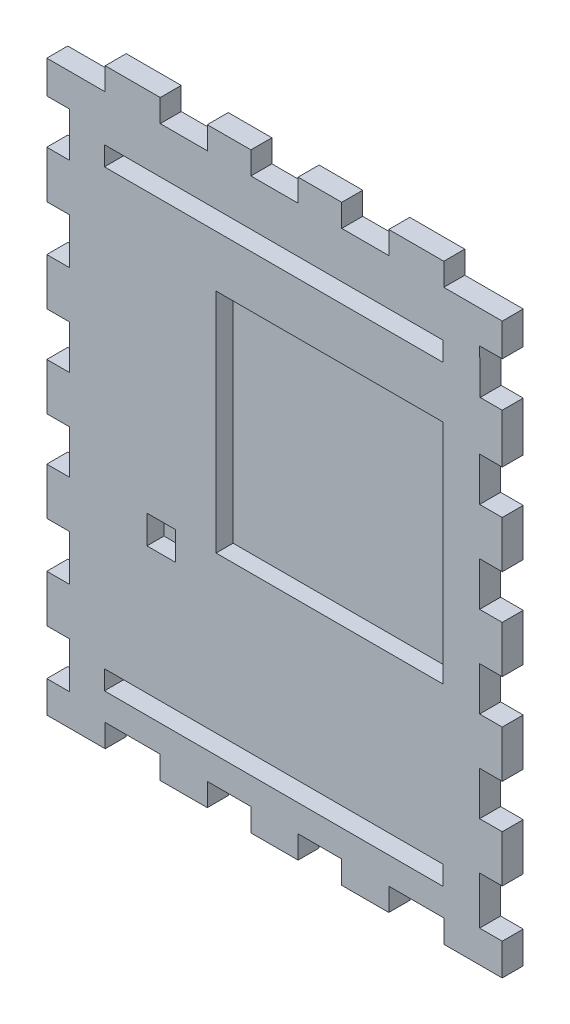
SolidWorks part; units mm, degrees
ref_plane "Front Plane" through (0, 0, 0) normal (0, 0, 1) x (1, 0, 0)
ref_plane "Top Plane" through (0, 0, 0) normal (0, 1, 0) x (1, 0, 0)
ref_plane "Right Plane" through (0, 0, 0) normal (1, 0, 0) x (0, 0, -1)
sketch "Model" plane through (0, 0, 0) normal (0, 0, 1) x (1, 0, 0)
  line L0 (11.6457, 131.1853) -> (7.6593, 131.1853)
  line L1 (7.6593, 131.1853) -> (7.6593, 139.4756)
  line L2 (7.6593, 139.4756) -> (11.6457, 139.4756)
  line L3 (11.6457, 139.4756) -> (11.6457, 147.1661)
  line L4 (11.6457, 147.1661) -> (7.6593, 147.1661)
  line L5 (7.6593, 147.1661) -> (7.6593, 155.4564)
  line L6 (7.6593, 155.4564) -> (11.6457, 155.4564)
  line L7 (11.6457, 155.4564) -> (11.6457, 163.1823)
  line L8 (11.6457, 163.1823) -> (7.6593, 163.1823)
  line L9 (7.6593, 163.1823) -> (7.6593, 171.4725)
  line L10 (7.6593, 171.4725) -> (11.6457, 171.4725)
  line L11 (87.9515, 101.1639) -> (77.6504, 101.1639)
  line L12 (77.6504, 101.1639) -> (77.6504, 105.1856)
  line L13 (77.6504, 105.1856) -> (67.949, 105.1856)
  line L14 (67.949, 105.1856) -> (67.949, 101.1639)
  line L15 (67.949, 101.1639) -> (59.6588, 101.1639)
  line L16 (59.6588, 101.1639) -> (59.6588, 105.1856)
  line L17 (59.6588, 105.1856) -> (51.9682, 105.1856)
  line L18 (51.9682, 105.1856) -> (51.9682, 101.1639)
  line L19 (51.9682, 101.1639) -> (43.6427, 101.1639)
  line L20 (43.6427, 101.1639) -> (43.6427, 105.1856)
  line L21 (43.6427, 105.1856) -> (35.9521, 105.1856)
  line L22 (35.9521, 105.1856) -> (35.9521, 101.1639)
  line L23 (35.9521, 101.1639) -> (27.6618, 101.1639)
  line L24 (27.6618, 101.1639) -> (27.6618, 105.1856)
  line L25 (27.6618, 105.1856) -> (17.9604, 105.1856)
  line L26 (17.9604, 105.1856) -> (17.9604, 101.1639)
  line L27 (17.9604, 101.1639) -> (7.6593, 101.1639)
  line L28 (87.9515, 179.1631) -> (83.9652, 179.1631)
  line L29 (83.9652, 179.1631) -> (83.9652, 171.4725)
  line L30 (83.9652, 171.4725) -> (87.9515, 171.4725)
  line L31 (87.9515, 171.4725) -> (87.9515, 163.1823)
  line L32 (87.9515, 163.1823) -> (83.9652, 163.1823)
  line L33 (83.9652, 163.1823) -> (83.9652, 155.4564)
  line L34 (83.9652, 155.4564) -> (87.9515, 155.4564)
  line L35 (87.9515, 155.4564) -> (87.9515, 147.1661)
  line L36 (87.9515, 147.1661) -> (83.9652, 147.1661)
  line L37 (83.9652, 147.1661) -> (83.9652, 139.4756)
  line L38 (83.9652, 139.4756) -> (87.9515, 139.4756)
  line L39 (87.9515, 139.4756) -> (87.9515, 131.1853)
  line L40 (87.9515, 131.1853) -> (83.9652, 131.1853)
  line L41 (87.9515, 201.4586) -> (77.6504, 201.4586)
  line L42 (77.6504, 201.4586) -> (77.6504, 205.445)
  line L43 (77.6504, 205.445) -> (67.949, 205.445)
  line L44 (67.949, 205.445) -> (67.949, 201.4586)
  line L45 (67.949, 201.4586) -> (59.6588, 201.4586)
  line L46 (59.6588, 201.4586) -> (59.6588, 205.445)
  line L47 (59.6588, 205.445) -> (51.9682, 205.445)
  line L48 (51.9682, 205.445) -> (51.9682, 201.4586)
  line L49 (51.9682, 201.4586) -> (43.6427, 201.4586)
  line L50 (43.6427, 201.4586) -> (43.6427, 205.445)
  line L51 (43.6427, 205.445) -> (35.9521, 205.445)
  line L52 (35.9521, 205.445) -> (35.9521, 201.4586)
  line L53 (35.9521, 201.4586) -> (27.6618, 201.4586)
  line L54 (27.6618, 201.4586) -> (27.6618, 205.445)
  line L55 (27.6618, 205.445) -> (17.9604, 205.445)
  line L56 (17.9604, 205.445) -> (17.9604, 201.4586)
  line L57 (17.9604, 201.4586) -> (7.6593, 201.4586)
  line L58 (17.8193, 193.3231) -> (77.5093, 193.3231)
  line L59 (77.5093, 193.3231) -> (77.5093, 189.9364)
  line L60 (77.5093, 189.9364) -> (17.8193, 189.9364)
  line L61 (17.8193, 189.9364) -> (17.8193, 193.3231)
  line L62 (17.8193, 113.3211) -> (77.5093, 113.3211)
  line L63 (77.5093, 113.3211) -> (77.5093, 109.9345)
  line L64 (77.5093, 109.9345) -> (17.8193, 109.9345)
  line L65 (17.8193, 109.9345) -> (17.8193, 113.3211)
  line L66 (11.6457, 179.5377) -> (7.6593, 179.5377)
  line L67 (7.6593, 179.5377) -> (7.6593, 187.8633)
  line L68 (7.6593, 187.8633) -> (11.6457, 187.8633)
  line L69 (11.6457, 187.8633) -> (11.6457, 195.686)
  line L70 (11.6457, 171.4725) -> (11.6457, 179.5377)
  line L71 (11.6457, 195.686) -> (7.6593, 195.686)
  line L72 (7.6593, 195.686) -> (7.6593, 201.4586)
  line L73 (11.6457, 114.7946) -> (7.6593, 114.7946)
  line L74 (7.6593, 114.7946) -> (7.6593, 123.1201)
  line L75 (7.6593, 123.1201) -> (11.6457, 123.1201)
  line L76 (11.6457, 123.1201) -> (11.6457, 131.1853)
  line L77 (7.6593, 101.1639) -> (7.6593, 106.7294)
  line L78 (7.6593, 106.7294) -> (11.6457, 106.7294)
  line L79 (11.6457, 106.7294) -> (11.6457, 114.7946)
  line L80 (83.9652, 131.1853) -> (83.9652, 123.4948)
  line L81 (83.9652, 123.4948) -> (87.9515, 123.4948)
  line L82 (87.9515, 123.4948) -> (87.9515, 115.2045)
  line L83 (87.9515, 115.2045) -> (83.9652, 115.2045)
  line L84 (83.9652, 115.2045) -> (83.9652, 106.7865)
  line L85 (83.9652, 106.7865) -> (87.9515, 106.7865)
  line L86 (87.9515, 106.7865) -> (87.9515, 101.1639)
  line L87 (83.9652, 195.686) -> (84.0662, 187.8513)
  line L88 (87.9515, 195.686) -> (83.9652, 195.686)
  line L89 (87.9515, 201.4586) -> (87.9515, 195.686)
  line L90 (87.9515, 187.8513) -> (87.9515, 179.1631)
  line L91 (84.0662, 187.8513) -> (88.0526, 187.8513)
extrude "Boss-Extrude1" add sketch "Model" along normal blind 3.7 contours L91 L87 L88 L89 L41 L42 L43 L44 L45 L46 L47 L48 L49 L50 L51 L52 L53 L54 L55 L56 L57 L72 L71 L69 L68 L67 L66 L70 L10 L9 L8 L7 L6 L5 L4 L3 L2 L1 L0 L76 L75 L74 L73 L79 L78 L77 L27 L26 L25 L24 L23
sketch "Sketch1" plane through (0, 0, 3.7) normal (0, 0, 1) x (1, 0, 0)
  line L0 (11.6457, 155.4564) -> (11.6457, 163.1823) construction
  line L1 (11.6457, 189.9364) -> (83.9652, 189.9364)
  line L2 (11.6457, 189.9364) -> (11.6457, 113.3211)
  line L3 (11.6457, 113.3211) -> (83.9652, 113.3211)
  line L4 (83.9652, 189.9364) -> (83.9652, 113.3211)
  line L5 (83.9652, 163.1823) -> (83.9652, 155.4564) construction
  line L7 (17.8193, 183.3211) -> (77.5093, 183.3211)
  line L8 (17.8193, 183.3211) -> (17.8193, 113.3211)
  line L9 (17.8193, 113.3211) -> (77.5093, 113.3211)
  line L10 (77.5093, 183.3211) -> (77.5093, 113.3211)
  line L11 (17.8193, 113.3211) -> (27.8193, 113.3211)
  line L12 (17.8193, 113.3211) -> (17.8193, 138.3211)
  line L13 (17.8193, 138.3211) -> (27.8193, 138.3211)
  line L14 (27.8193, 113.3211) -> (27.8193, 138.3211)
  line L15 (25.3193, 140.8211) -> (30.3193, 140.8211)
  line L16 (25.3193, 140.8211) -> (25.3193, 135.8211)
  line L17 (25.3193, 135.8211) -> (30.3193, 135.8211)
  line L18 (30.3193, 140.8211) -> (30.3193, 135.8211)
  line L19 (25.3193, 140.8211) -> (30.3193, 135.8211) construction
  line L20 (25.3193, 135.8211) -> (30.3193, 140.8211) construction
  line L21 (77.5093, 113.3211) -> (37.5093, 113.3211)
  line L22 (77.5093, 113.3211) -> (77.5093, 180.8211)
  line L23 (77.5093, 180.8211) -> (37.5093, 180.8211)
  line L24 (37.5093, 113.3211) -> (37.5093, 180.8211)
  line L25 (37.5093, 180.8211) -> (77.5093, 180.8211)
  line L26 (37.5093, 180.8211) -> (37.5093, 140.8211)
  line L27 (37.5093, 140.8211) -> (77.5093, 140.8211)
  line L28 (77.5093, 180.8211) -> (77.5093, 140.8211)
  dimension "D1" = 70
  dimension "D2" = 59.69
  dimension "D3" = 25
  dimension "D4" = 10
  dimension "D5" = 5
  dimension "D6" = 5
  dimension "D7" = 40
  dimension "D8" = 67.5
  dimension "D9" = 40
extrude "Cut-Extrude1" cut sketch "Sketch1" against normal blind 3 contours L16 L17 L14 L13 | L18 L15 L16 L13 L14 L17 | L24 L27 L10 L23
